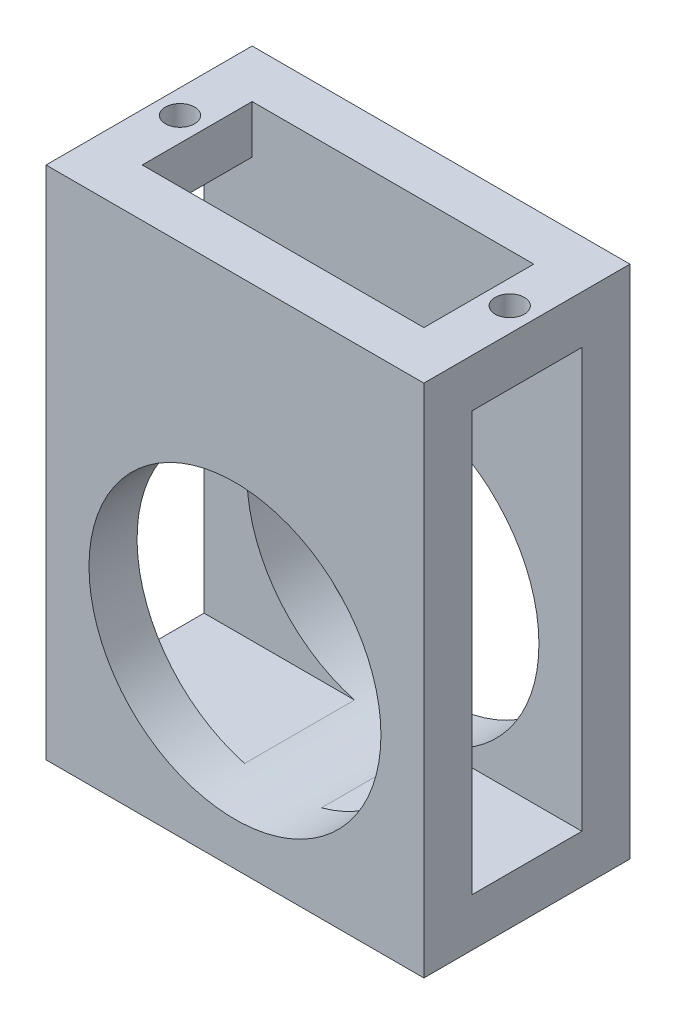
SolidWorks part; units mm, degrees
ref_plane "Front Plane" through (0, 0, 0) normal (0, 0, 1) x (1, 0, 0)
ref_plane "Top Plane" through (0, 0, 0) normal (0, 1, 0) x (1, 0, 0)
ref_plane "Right Plane" through (0, 0, 0) normal (1, 0, 0) x (0, 0, -1)
sketch "Sketch1" plane through (0, 0, 0) normal (0, 0, 1) x (1, 0, 0)
  line L1 (-27.5, 47.5) -> (27.5, 47.5)
  line L2 (-27.5, 47.5) -> (-27.5, -27.5)
  line L3 (-27.5, -27.5) -> (27.5, -27.5)
  line L4 (27.5, 47.5) -> (27.5, -27.5)
  dimension "D1" = 55
  dimension "D2" = 75
  dimension "D3" = 27.5
  dimension "D4" = 27.5
extrude "Boss-Extrude1" add sketch "Sketch1" along normal blind 30
sketch "Sketch2" plane through (0, 0, 30) normal (0, 0, 1) x (1, 0, 0)
  circle A0 centre (0, 0) radius 21.25
  dimension "D1" = 42.5
extrude "Cut-Extrude1" cut sketch "Sketch2" against normal blind 30
sketch "Sketch3" plane through (0, 47.5, 0) normal (0, 1, 0) x (1, 0, 0)
  line L0 (27.5, 0) -> (-27.5, 0) construction
  line L1 (-20.5, -7) -> (20.5, -7)
  line L2 (-20.5, -7) -> (-20.5, -23)
  line L3 (-20.5, -23) -> (20.5, -23)
  line L4 (20.5, -7) -> (20.5, -23)
  line L5 (-27.5, -30) -> (-27.5, 0) construction
  dimension "D1" = 16
  dimension "D2" = 7
  dimension "D3" = 41
  dimension "D4" = 7
extrude "Cut-Extrude2" cut sketch "Sketch3" against normal blind 60
sketch "Sketch4" plane through (27.5, 0, 0) normal (1, 0, 0) x (0, 0, -1)
  line L0 (-30, 47.5) -> (0, 47.5) construction
  line L1 (-23, 40.5) -> (-7, 40.5)
  line L2 (-23, 40.5) -> (-23, -20.5)
  line L3 (-23, -20.5) -> (-7, -20.5)
  line L4 (-7, 40.5) -> (-7, -20.5)
  line L5 (0, -27.5) -> (0, 47.5) construction
  line L6 (-30, -27.5) -> (0, -27.5) construction
  dimension "D1" = 7
  dimension "D2" = 7
  dimension "D3" = 16
  dimension "D4" = 7
extrude "Cut-Extrude3" cut sketch "Sketch4" against normal blind 60
sketch "Sketch5" plane through (0, 47.5, 0) normal (0, 1, 0) x (1, 0, 0)
  line L0 (-20.5, -7) -> (-20.5, -23) construction
  line L1 (20.5, -23) -> (20.5, -7) construction
  line L2 (20.5, -7) -> (-20.5, -7) construction
  circle A0 centre (-24, -14) radius 2.125
  circle A1 centre (24, -14) radius 2.125
  dimension "D1" = 4.25
  dimension "D2" = 4.25
  dimension "D3" = 3.5
  dimension "D4" = 3.5
  dimension "D5" = 7
extrude "Cut-Extrude4" cut sketch "Sketch5" against normal blind 10
